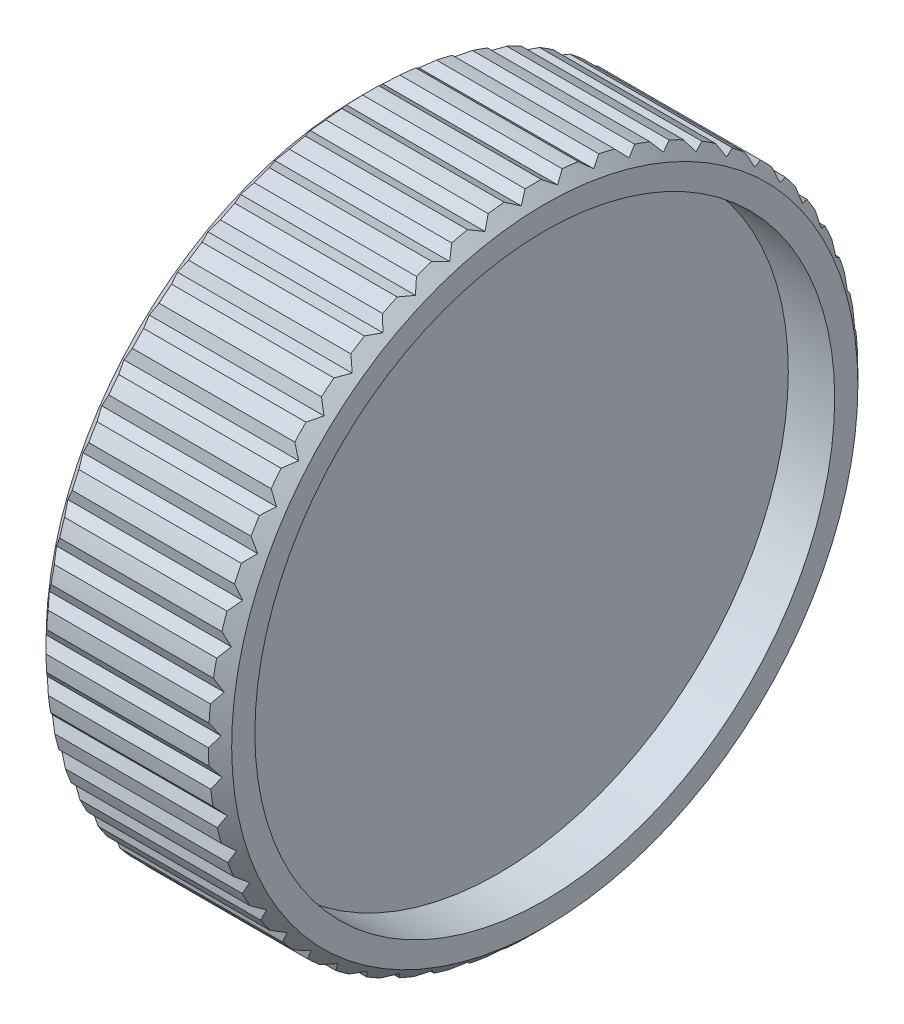
SolidWorks part; units mm, degrees
ref_plane "Front Plane" through (0, 0, 0) normal (0, 0, 1) x (1, 0, 0)
ref_plane "Top Plane" through (0, 0, 0) normal (0, 1, 0) x (1, 0, 0)
ref_plane "Right Plane" through (0, 0, 0) normal (1, 0, 0) x (0, 0, -1)
sketch "Sketch1" plane through (0, 0, 0) normal (1, 0, 0) x (0, 0, -1)
  circle A0 centre (0, 0) radius 28
  dimension "D1" = 56
extrude "Boss-Extrude1" add sketch "Sketch1" along normal mid plane 16
sketch "Sketch2" plane through (8, 0, 0) normal (1, 0, 0) x (0, 0, -1)
  circle A0 centre (0, 38) radius 15
  dimension "D1" = 30
  dimension "D2" = 38
extrude "Cut-Extrude1" [suppressed] cut sketch "Sketch2" against normal through all
chamfer "Chamfer1" distance 1 angle 45 2 edges at (-8, 0, -28) (8, 0, -28)
sketch "Sketch3" plane through (8, 0, 0) normal (1, 0, 0) x (0, 0, -1)
  circle A1 centre (0, 0) radius 25
  circle A10 centre (0, 0) radius 25
  dimension "D1" = 2
extrude "Cut-Extrude2" cut sketch "Sketch3" against normal blind 4
mirror "Mirror1" about plane through (0, 0, 0) normal (1, 0, 0) of "Cut-Extrude2"
sketch "Sketch4" plane through (8, 0, 0) normal (1, 0, 0) x (0, 0, -1)
  line L0 (0, -27.4641) -> (-8.6603, -32.4641)
  line L1 (-8.6603, -32.4641) -> (8.6603, -32.4641)
  line L2 (8.6603, -32.4641) -> (0, -27.4641)
  circle A0 centre (0, 0) radius 27 construction
  dimension "D1" = 120
  dimension "D2" = 5
extrude "Cut-Extrude3" cut sketch "Sketch4" against normal through all
pattern_circular "CirPattern1" count 55 over 360 about axis through (0, 0, 0) along (1, 0, 0) of "Cut-Extrude3"
